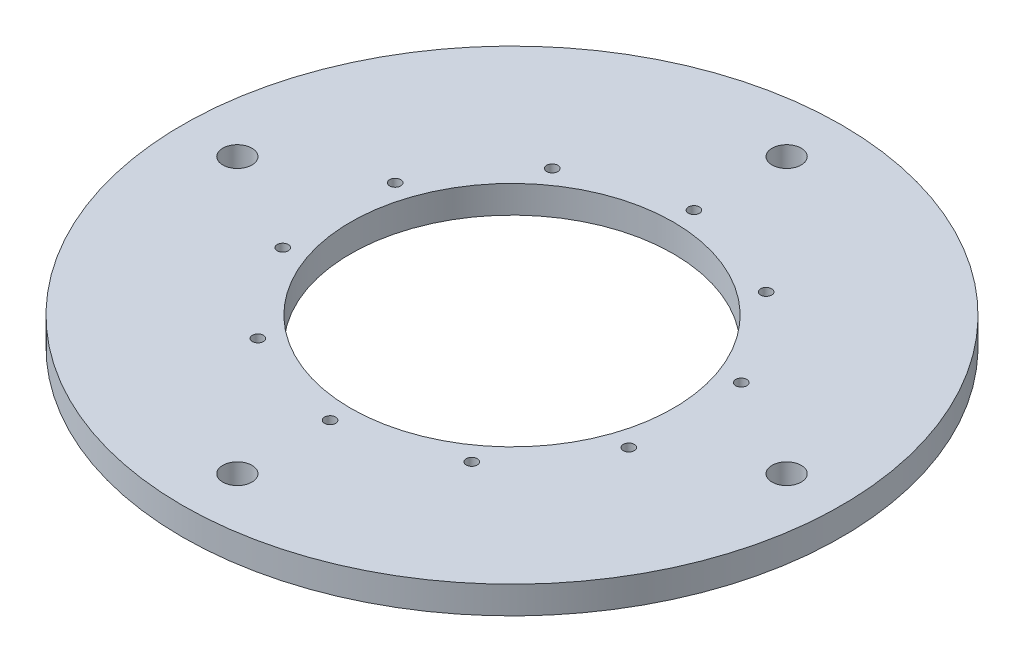
SolidWorks part; units mm, degrees
material "Plain Carbon Steel"
ref_plane "Front Plane" through (0, 0, 0) normal (0, 0, 1) x (1, 0, 0)
ref_plane "Top Plane" through (0, 0, 0) normal (0, 1, 0) x (1, 0, 0)
ref_plane "Right Plane" through (0, 0, 0) normal (1, 0, 0) x (0, 0, -1)
sketch "Sketch1" plane through (0, 0, 0) normal (0, 1, 0) x (1, 0, 0)
  circle A3 centre (0, 0) radius 152.4
  circle A8 centre (0, 0) radius 127 construction
  circle A20 centre (0, 0) radius 74.6125
  circle A23 centre (0, 0) radius 84.1375 construction
  point P2 (0, 127)
  point P5 (0, 84.1375)
  dimension "Diameter_Takeout_BoltCircle" = 254
  dimension "Diameter_ThrustPlate" = 304.8
  dimension "D2" = 168.275
  dimension "D4" = 149.225
extrude "ThrustPlate_TC3" add sketch "Sketch1" against normal blind 12.7 separate body
sketch "Sketch11" plane through (0, 0, 0) normal (0, 1, 0) x (1, 0, 0)
  point P0 (0, 127)
hole_wizard "UNDEF_Clearance_ThrustPlate" positions "Sketch11" profile "Sketch12" hole size "1/2" standard "ANSI Inch" end condition through all
sketch "Sketch12" plane through (0, 0, -127) normal (1, 0, 0) x (0, 0, 1)
  line L0 (0, 0) -> (0, 12.7)
  line L1 (0, 12.7) -> (6.7462, 12.7)
  line L2 (6.7462, 12.7) -> (6.7462, 0)
  line L5 (6.7462, 0) -> (0, 0)
  line L11 (0, -6.35) -> (0, 107.95) construction
  dimension "Thru Hole Dia." = 13.4925
  dimension "Thru Hole Depth" = 12.7
pattern_circular "Clearance_ThrustPlate_Pattern" count 4 over 360 about axis through (0, 0, 0) along (0, 1, 0) of "UNDEF_Clearance_ThrustPlate"
sketch "Sketch22" plane through (0, 0, 0) normal (0, 1, 0) x (1, 0, 0)
  point P0 (0, 84.1375)
hole_wizard "#10 Clearance Hole1" positions "Sketch22" profile "Sketch23" hole size "#10" standard "ANSI Inch" end condition through all
sketch "Sketch23" plane through (0, 0, -84.1375) normal (1, 0, 0) x (0, 0, 1)
  line L0 (0, 0) -> (0, 12.7)
  line L1 (0, 12.7) -> (2.5527, 12.7)
  line L2 (2.5527, 12.7) -> (2.5527, 0)
  line L5 (2.5527, 0) -> (0, 0)
  line L11 (0, -6.35) -> (0, 107.95) construction
  dimension "Thru Hole Dia." = 5.1054
  dimension "Thru Hole Depth" = 12.7
pattern_circular "CirPattern1" count 10 over 360 about axis through (0, 0, 0) along (0, 1, 0) of "#10 Clearance Hole1"
equation "\"Diameter_BackPlate\"= 6.5"
equation "\"VAR_Diameter_BackPlate_BoltCircle\"= 6"
equation "\"VAR_Diameter_FuelOuterPlenum\"= 4.4"
equation "\"Thickness_ThrustPlate\"= 0.5'undetermined"
equation "\"Diameter_ThrustPlate\"= 12'defined"
equation "\"Diameter_Takeout_BoltCicle\"= 10'defined"
equation "\"Diameter_Takeout_BoltCircle@Sketch1\"=\"Diameter_Takeout_BoltCicle\""
equation "\"Diameter_ThrustPlate@Sketch1\"=\"Diameter_ThrustPlate\""
equation "\"D1@ThrustPlate_TC3\"=\"Thickness_ThrustPlate\""
equation "\"VAR_Diameter_CBORE\"= 0.44'undetermined"
equation "\"VAR_Diameter_Clearance_ThrustPlate\"= 0.25'undetermined"
equation "\"NumberBolts_BackPlate\"= 20"
equation "\"NumberBolts_Takeout\"= 4'defined"
equation "\"D1@Clearance_ThrustPlate_Pattern\"=\"NumberBolts_Takeout\""
